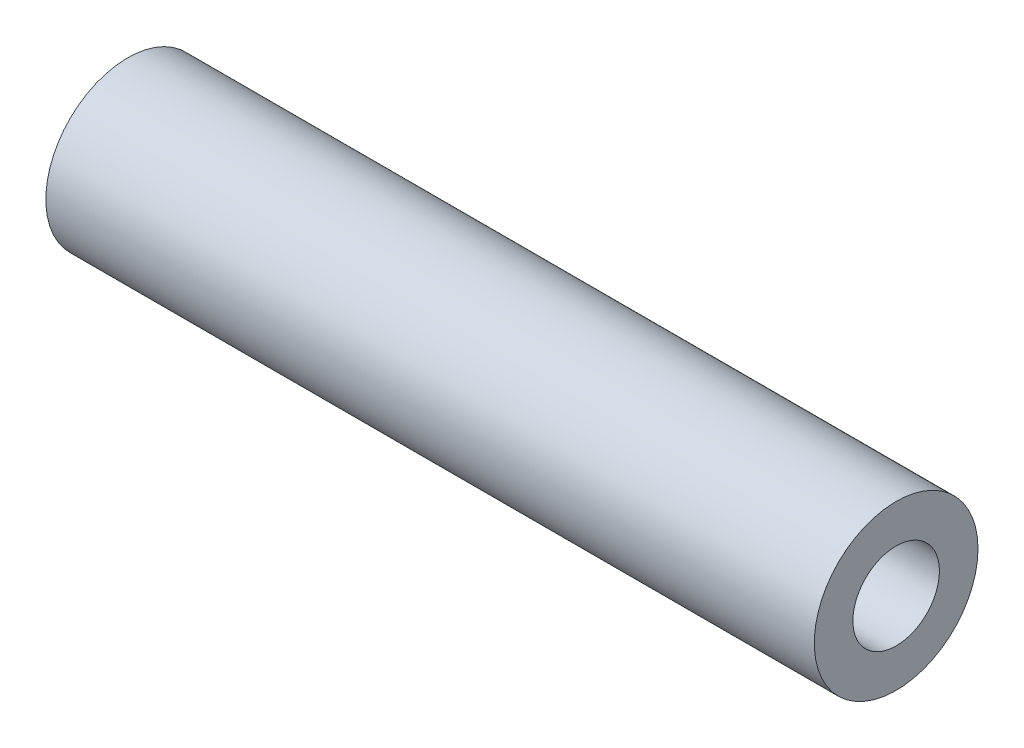
SolidWorks part; units mm, degrees
ref_plane "Front Plane" through (0, 0, 0) normal (0, 0, 1) x (1, 0, 0)
ref_plane "Top Plane" through (0, 0, 0) normal (0, 1, 0) x (1, 0, 0)
ref_plane "Right Plane" through (0, 0, 0) normal (1, 0, 0) x (0, 0, -1)
sketch "Sketch1" plane through (0, 0, 0) normal (1, 0, 0) x (0, 0, -1)
  circle A0 centre (0, 0) radius 3.0861
  circle A1 centre (0, 0) radius 1.632
  dimension "D1" = 3.2639
  dimension "D2" = 6.1722
extrude "Boss-Extrude1" add sketch "Sketch1" along normal blind 28.9687
